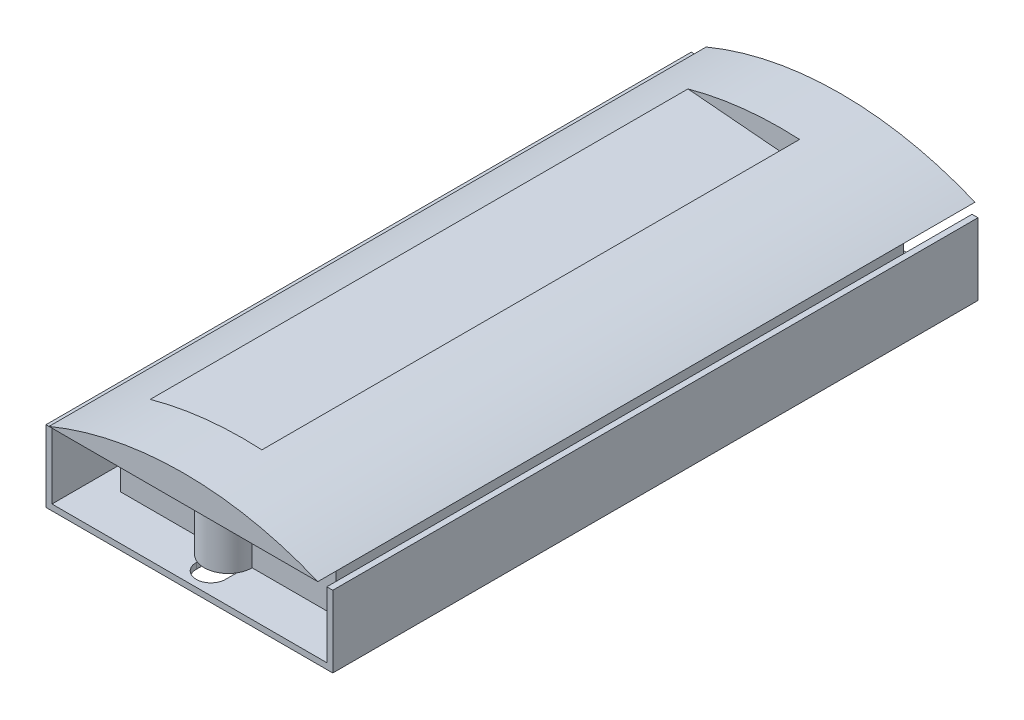
SolidWorks part; units mm, degrees
ref_plane "前视基准面" through (0, 0, 0) normal (0, 0, 1) x (1, 0, 0)
ref_plane "上视基准面" through (0, 0, 0) normal (0, 1, 0) x (1, 0, 0)
ref_plane "右视基准面" through (0, 0, 0) normal (1, 0, 0) x (0, 0, -1)
sketch "草图1" plane through (0, 0, 0) normal (0, 0, 1) x (1, 0, 0)
  line L0 (0, 0) -> (45, 0)
  arc A0 (0, 0) -> (45, 0) centre (22.5, -54) cw
  point P3 (22.5, 4.5)
  dimension "D1" = 45
  dimension "D2" = 4.5
extrude "凸台-拉伸1" add sketch "草图1" along normal blind 110
sketch "草图2" plane through (0, 0, 0) normal (0, -1, 0) x (-1, 0, 0)
  line L0 (0, -55) -> (-45, -55) construction
  line L1 (0, -110) -> (0, 0) construction
  line L2 (-45, -110) -> (-45, 0) construction
  line L3 (-22.5, -7.5) -> (-22.5, -102.5) construction
  line L4 (-4.5, -7.5) -> (-40.5, -7.5)
  line L5 (-4.5, -7.5) -> (-4.5, -102.5)
  line L6 (-4.5, -102.5) -> (-40.5, -102.5)
  line L7 (-40.5, -7.5) -> (-40.5, -102.5)
  line L8 (-4.5, -7.5) -> (-40.5, -102.5) construction
  line L9 (-4.5, -102.5) -> (-40.5, -7.5) construction
  line L10 (-18.5, -7.5) -> (-18.5, -102.5)
  line L11 (-26.5, -7.5) -> (-26.5, -102.5)
  arc A0 (-18.5, -7.5) -> (-26.5, -7.5) centre (-22.5, -7.5) ccw
  arc A1 (-26.5, -102.5) -> (-18.5, -102.5) centre (-22.5, -102.5) ccw
  point P6 (-22.5, -55)
  point P13 (-22.5, -55)
  point P18 (-22.5, -106.5)
  point P19 (-22.5, -3.5)
  dimension "D1" = 36
  dimension "D2" = 95
  dimension "D3" = 8
  dimension "D4" = 103
extrude "凸台-拉伸2" add sketch "草图2" along normal blind 11 contours L4 L10 L6 L5 | L4 L11 L6 L10 | L6 A1 | L11 L4 L7 L6 | L4 A0
sketch "草图3" plane through (0, -11, 0) normal (0, -1, 0) x (1, 0, 0)
  circle A0 centre (22.5, 102.5) radius 1.6
  circle A1 centre (22.5, 7.5) radius 1.6
  dimension "D1" = 3.2
extrude "切除-拉伸1" cut sketch "草图3" against normal blind 11
ref_plane "基准面1" through (0, -12, 0) normal (0, -1, 0) x (-1, 0, 0)
sketch "草图4" plane through (0, -12, 0) normal (0, -1, 0) x (-1, 0, 0)
  line L0 (-40.5, -55) -> (-4.5, -55) construction
  line L1 (-40.5, -7.5) -> (-40.5, -102.5) construction
  line L2 (-4.5, -7.5) -> (-4.5, -102.5) construction
  line L3 (-22.5, -4.6) -> (-22.5, -10.4) construction
  line L4 (-46.5, -109) -> (1.5, -109)
  line L5 (-46.5, -109) -> (-46.5, -1)
  line L6 (-46.5, -1) -> (1.5, -1)
  line L7 (1.5, -109) -> (1.5, -1)
  line L8 (-46.5, -109) -> (1.5, -1) construction
  line L9 (-46.5, -1) -> (1.5, -109) construction
  line L10 (-20.05, -4.6) -> (-20.05, -10.4)
  line L11 (-24.95, -4.6) -> (-24.95, -10.4)
  line L12 (-22.5, -105.4) -> (-22.5, -99.6) construction
  line L13 (-20.05, -105.4) -> (-20.05, -99.6)
  line L14 (-24.95, -105.4) -> (-24.95, -99.6)
  arc A0 (-20.05, -4.6) -> (-24.95, -4.6) centre (-22.5, -4.6) ccw
  arc A1 (-24.95, -10.4) -> (-20.05, -10.4) centre (-22.5, -10.4) ccw
  arc A2 (-20.05, -105.4) -> (-24.95, -105.4) centre (-22.5, -105.4) cw
  arc A3 (-24.95, -99.6) -> (-20.05, -99.6) centre (-22.5, -99.6) cw
  point P6 (-22.5, -55)
  point P13 (-22.5, -7.5)
  point P21 (-22.5, -102.5)
  dimension "D1" = 48
  dimension "D2" = 108
  dimension "D3" = 4.9
  dimension "D4" = 5.8
extrude "凸台-拉伸3" add sketch "草图4" along normal blind 1 separate body
sketch "草图5" plane through (0, 0, 109) normal (0, 0, 1) x (1, 0, 0)
  line L0 (22.5, -13) -> (22.5, -16.1921) construction
  line L1 (-1.5, -13) -> (-0.5, -13)
  line L2 (-1.5, -13) -> (-1.5, -1)
  line L3 (-1.5, -1) -> (-0.5, -1)
  line L4 (-0.5, -13) -> (-0.5, -1)
  line L5 (46.5, -13) -> (-1.5, -13) construction
  line L6 (45.5, -13) -> (45.5, -1)
  line L7 (46.5, -1) -> (45.5, -1)
  line L8 (46.5, -13) -> (46.5, -1)
  line L9 (46.5, -13) -> (45.5, -13)
  dimension "D1" = 1
  dimension "D2" = 12
extrude "凸台-拉伸4" add sketch "草图5" against normal up to surface (108 mm away) up to face at (22.5, -12.5, 1)
ref_plane "基准面2" through (0, 0, 55) normal (0, 0, -1) x (-1, 0, 0)
sketch "草图6" plane through (0, 0, 55) normal (0, 0, -1) x (-1, 0, 0)
  line L0 (-25.6355, 4.4159) -> (-28.8797, 3.1149)
  line L3 (-21.709, 7.7542) -> (-25.6355, 4.4159)
  line L4 (-28.8797, 0.4972) -> (-5.3884, 2.5313)
  line L5 (-21.709, 7.7542) -> (-5.3884, 2.5313)
  arc A0 (0, 0) -> (-45, 0) centre (-22.5, -54) ccw construction
  arc A1 (-28.8797, 0.4972) -> (-28.8797, 3.1149) centre (-28.3548, 1.8061) cw
  point P6 (-28.8797, 3.1149)
  point P7 (-5.3884, 2.5313)
  point P8 (-28.8797, 0.4972)
extrude "切除-拉伸2" cut sketch "草图6" against normal blind 45 and the other way blind 45
